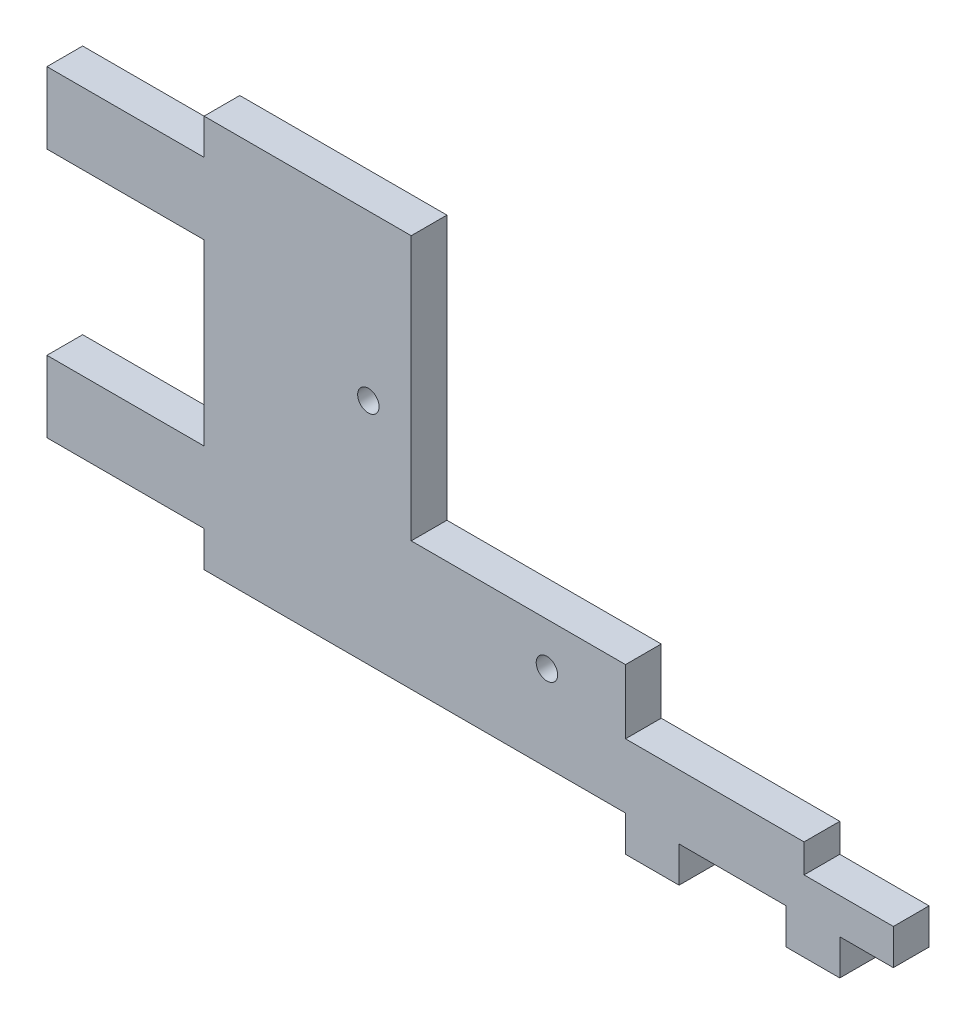
SolidWorks part; units mm, degrees
ref_plane "Plan de face" through (0, 0, 0) normal (0, 0, 1) x (1, 0, 0)
ref_plane "Plan de dessus" through (0, 0, 0) normal (0, 1, 0) x (1, 0, 0)
ref_plane "Plan de droite" through (0, 0, 0) normal (1, 0, 0) x (0, 0, -1)
sketch "Esquisse1" plane through (0, 0, 0) normal (0, 0, 1) x (1, 0, 0)
  line L1 (0, 0) -> (37, 0)
  line L2 (0, 0) -> (0, 55)
  line L3 (0, 55) -> (12, 55)
  line L4 (37, 0) -> (37, 18)
  line L6 (12, 55) -> (12, 18)
  line L7 (12, 18) -> (37, 18)
  circle A0 centre (6, 32) radius 1.5
  circle A1 centre (31, 12) radius 1.5
  dimension "D3" = 20
  dimension "D4" = 3
  dimension "D1" = 6
  dimension "D2" = 55
  dimension "D5" = 12
  dimension "D7" = 25
  dimension "D8" = 6
  dimension "D9" = 6
extrude "Boss.-Extru.1" add sketch "Esquisse1" along normal blind 5
sketch "Esquisse2" plane through (0, 0, 5) normal (0, 0, 1) x (1, 0, 0)
  line L0 (37, 18) -> (12, 18) construction
  line L1 (37, 0) -> (42, 0)
  line L2 (37, 0) -> (37, 18)
  line L3 (49.5, 0) -> (64.5, 0)
  line L4 (12, 55) -> (0, 55) construction
  line L5 (72, 0) -> (72, -5)
  line L6 (72, -5) -> (64.5, -5)
  line L7 (64.5, 0) -> (64.5, -5)
  line L8 (72, 0) -> (79.5, 0)
  line L9 (49.5, 0) -> (49.5, -5)
  line L10 (49.5, -5) -> (42, -5)
  line L11 (42, 0) -> (42, -5)
  line L12 (0, 0) -> (-17, 0)
  line L13 (0, 0) -> (0, 55)
  line L14 (0, 55) -> (-17, 55)
  line L15 (-17, 50) -> (-17, 55)
  line L16 (-17, 5) -> (-39, 5)
  line L17 (-17, 15) -> (-17, 40)
  line L18 (37, 18) -> (42, 18)
  line L19 (-17, 15) -> (-39, 15)
  line L20 (-17, 0) -> (-17, 5)
  line L21 (-39, 5) -> (-39, 15)
  line L22 (-17, 50) -> (-39, 50)
  line L23 (42, 18) -> (42, 9)
  line L24 (-17, 40) -> (-39, 40)
  line L25 (-39, 50) -> (-39, 40)
  line L26 (42, 9) -> (67, 9)
  line L27 (67, 9) -> (67, 5)
  line L28 (67, 5) -> (79.5, 5)
  line L29 (79.5, 5) -> (79.5, 0)
  circle A0 centre (31, 12) radius 1.5 construction
  dimension "D7" = 11
  dimension "D1" = 42.5
  dimension "D2" = 7.5
  dimension "D3" = 5
  dimension "D4" = 5
  dimension "D5" = 15
  dimension "D6" = 5
  dimension "D8" = 10
  dimension "D9" = 5
  dimension "D10" = 25
  dimension "D11" = 22
  dimension "D12" = 17
  dimension "D13" = 3
  dimension "D14" = 25
extrude "Boss.-Extru.2" add sketch "Esquisse2" against normal blind 5
